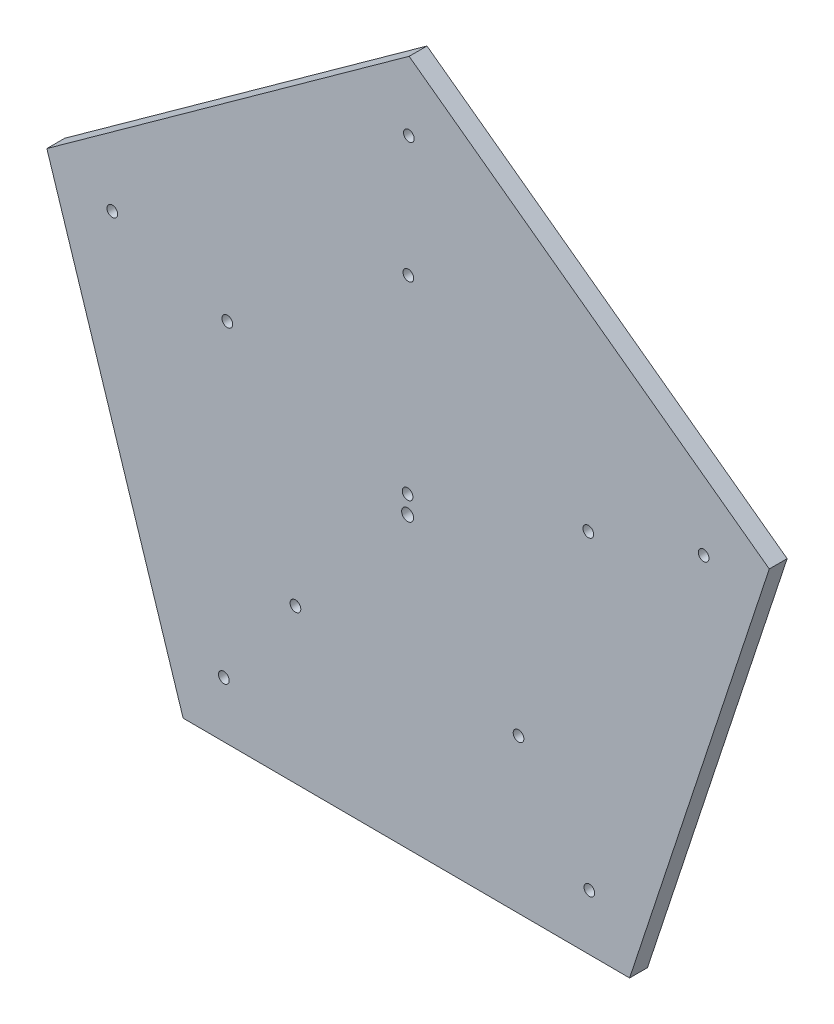
SolidWorks part; units mm, degrees
ref_plane "Front Plane" through (0, 0, 0) normal (0, 0, 1) x (1, 0, 0)
ref_plane "Top Plane" through (0, 0, 0) normal (0, 1, 0) x (1, 0, 0)
ref_plane "Right Plane" through (0, 0, 0) normal (1, 0, 0) x (0, 0, -1)
sketch "Sketch1" plane through (0, 0, 0) normal (0, 0, 1) x (1, 0, 0)
  line L1 (-37.7065, -51.4643) -> (37.2935, -51.7644)
  line L2 (37.2935, -51.7644) -> (60.7552, 19.4722)
  line L3 (60.7552, 19.4722) -> (0.2553, 63.7988)
  line L4 (0.2553, 63.7988) -> (-60.5974, 19.9577)
  line L5 (-60.5974, 19.9577) -> (-37.7065, -51.4643)
  circle A0 centre (0, 0) radius 51.6147 construction
  dimension "D1" = 75
extrude "Boss-Extrude1" add sketch "Sketch1" along normal blind 3 contours L4 L5 L1 L2 L3
sketch "Sketch3" plane through (0, 0, 3) normal (0, 0, 1) x (1, 0, 0)
  circle A0 centre (0, 0) radius 0.9
  point P29 (0, 0)
extrude "Cut-Extrude1" cut sketch "Sketch3" against normal blind 3 contours A0
sketch "Sketch5" plane through (0, 0, 3) normal (0, 0, 1) x (1, 0, 0)
  line L0 (-60.5974, 19.9577) -> (49.0243, -16.1461) construction
  line L2 (0.2553, 63.7988) -> (-0.2065, -51.6143) construction
  line L4 (30.5052, 41.6355) -> (-37.7065, -51.4643) construction
  line L6 (60.7552, 19.4722) -> (-49.152, -15.7533) construction
  line L8 (37.2935, -51.7644) -> (-30.1711, 41.8782) construction
  line L11 (-37.7065, -51.4643) -> (37.2935, -51.7644) construction
  line L16 (0.2553, 63.7988) -> (-60.5974, 19.9577) construction
  line L17 (37.2935, -51.7644) -> (60.7552, 19.4722) construction
  line L18 (60.7552, 19.4722) -> (0.2553, 63.7988) construction
  line L19 (-60.5974, 19.9577) -> (-37.7065, -51.4643) construction
  circle A0 centre (0, 0) radius 20
  circle A3 centre (-30.8649, -42.1264) radius 8.6076
  circle A4 centre (-18.8407, -25.715) radius 13
  circle A5 centre (-30.8649, -42.1264) radius 0.9
  circle A6 centre (-18.8407, -25.715) radius 0.9
extrude "Cut-Extrude2" cut sketch "Sketch5" against normal blind 3 contours A5 | A6
pattern_circular "CirPattern1" count 5 over 360 about axis through (0, 0, 0) along (0, 0, 1) of "Cut-Extrude2"
sketch "Sketch6" plane through (0, 0, 0) normal (0, 0, -1) x (-1, 0, 0)
  line L0 (0, 0) -> (0, -3) construction
  circle A0 centre (0, -3) radius 1
  dimension "D1" = 3
extrude "Cut-Extrude3" cut sketch "Sketch6" against normal blind 3 contours A0
